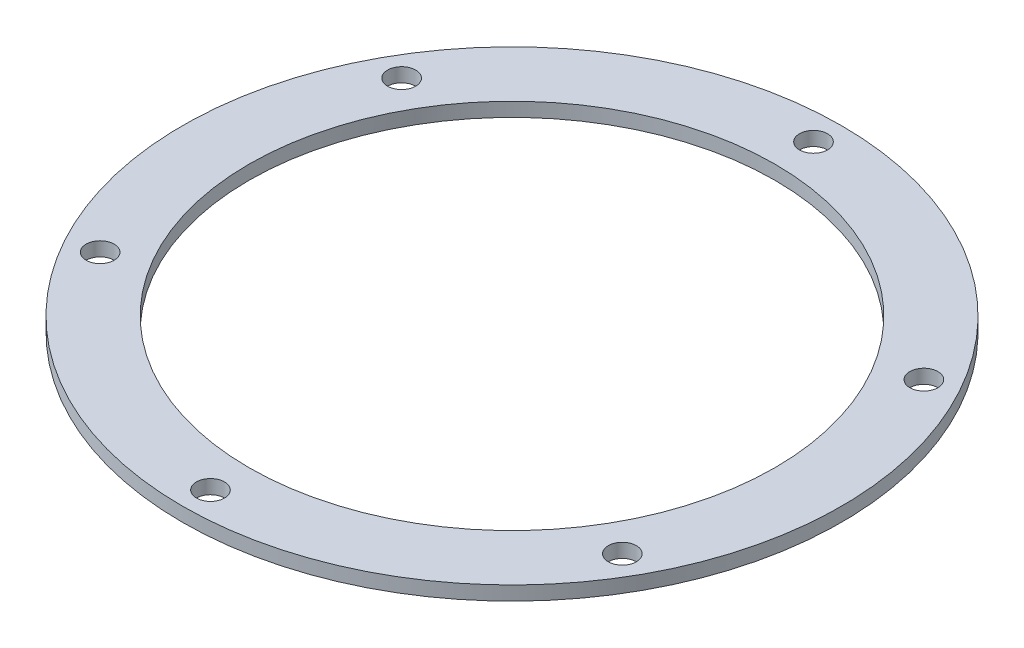
SolidWorks part; units mm, degrees
material "PLA"
ref_plane "Front Plane" through (0, 0, 0) normal (0, 0, 1) x (1, 0, 0)
ref_plane "Top Plane" through (0, 0, 0) normal (0, 1, 0) x (1, 0, 0)
ref_plane "Right Plane" through (0, 0, 0) normal (1, 0, 0) x (0, 0, -1)
sketch "Sketch1" plane through (0, 0, 0) normal (0, 1, 0) x (1, 0, 0)
  circle A0 centre (0, 0) radius 47
  circle A1 centre (0, 0) radius 37.5
  circle A2 centre (0, 0) radius 43 construction
  circle A3 centre (0, 43) radius 2
  circle A4 centre (37.2391, 21.5) radius 2
  circle A5 centre (37.2391, -21.5) radius 2
  circle A6 centre (0, -43) radius 2
  circle A7 centre (-37.2391, -21.5) radius 2
  circle A8 centre (-37.2391, 21.5) radius 2
  point P19 (0, 0)
  dimension "D1" = 94
  dimension "D2" = 75
  dimension "D3" = 86
  dimension "D4" = 4
  dimension "D5" = 6
extrude "Boss-Extrude1" add sketch "Sketch1" along normal blind 2
equation "\"Np_b\" = 48"
equation "\"Np_s\" = 28"
equation "\"Nr_b\" = 152"
equation "\"Nr_s\" = 132"
equation "\"Ns\" = 56"
equation "\"Motor_case_ID\" = 96.8"
equation "\"Motor_case_OD_base_to_chamfer\" = 5"
equation "\"Motor_case_OD_max\" = 111.3"
equation "\"Motor_case_thickness\" = 2.5"
equation "\"air_flow_hole_offset\" = 3"
equation "\"standard_bearing_insertion_chamfer\" = 0.5"
equation "\"alpha_p_b\" = 0.8539582918412414"
equation "\"alpha_p_s\" = 0.8539582918412485"
equation "\"alpha_r_b\" = 0.8539582918412236"
equation "\"alpha_r_s\" = 0.8539582918412449"
equation "\"alpha_s\" = 0.8539582918412485"
equation "\"base_plate_thickness\" = 4"
equation "\"bearing_ID\" = 60"
equation "\"bearing_OD\" = 78"
equation "\"bearing_height\" = 10"
equation "\"bearing mount thickness\" = 8"
equation "\"bearing_retainer_thickness\" = 2"
equation "\"beta_p_b\" = 2.042083416317517"
equation "\"beta_p_s\" = 4.720654844888932"
equation "\"beta_r_b\" = 2.8921271099982366"
equation "\"beta_r_s\" = 3.071552947318853"
equation "\"beta_s\" = 1.5063691306032174"
equation "\"carrier_PCD\" = 52.0"
equation "\"carrier_bearing_step_width\" = 1.5"
equation "\"carrier_small_ring_inner_bearing_ID\" = 20"
equation "\"carrier_small_ring_inner_bearing_OD\" = 32"
equation "\"carrier_small_ring_inner_bearing_flap\" = 2"
equation "\"carrier_small_ring_inner_bearing_height\" = 7"
equation "\"carrier_thickness\" = 4"
equation "\"carrier_trapezoidal_support_hole_PCD_offset_bearing_ID\" = 4"
equation "\"carrier_trapezoidal_support_hole_dia\" = 3"
equation "\"carrier_trapezoidal_support_hole_socket_head_dia\" = 5.5"
equation "\"carrier_trapezoidal_support_hole_wrench_size\" = 5.5"
equation "\"carrier_trapezoidal_support_sun_offset\" = 5"
equation "\"case_dist\" = 6.5"
equation "\"case_mounting_PCD\" = 103.8"
equation "\"case_mounting_bolt_depth\" = 4.5"
equation "\"case_mounting_hole_allen_socket_dia\" = 5.5"
equation "\"case_mounting_hole_dia\" = 3"
equation "\"case_mounting_hole_shift\" = 1.0"
equation "\"case_mounting_nut_clearance\" = 2"
equation "\"case_mounting_nut_thickness\" = 2.4"
equation "\"case_mounting_surface_height\" = 4"
equation "\"case_mounting_wrench_size\" = 5.5"
equation "\"central_hole_offset_from_motor_mount_PCD\" = 5"
equation "\"clearance_case_mount_holes_shell_thickness\" = 1"
equation "\"clearance_motor_and_case\" = 5"
equation "\"clearance_planet\" = 1.5"
equation "\"clearance_sun_coupler_sec_carrier\" = 1.5"
equation "\"clr_tip_root\" = 0.125"
equation "\"clr_tip_root_s\" = 0.125"
equation "\"db_p_b\" = 22.552622898861802"
equation "\"db_p_s\" = 13.155696691002717"
equation "\"db_r_b\" = 71.41663917972905"
equation "\"db_r_s\" = 62.01971297186996"
equation "\"db_s\" = 26.311393382005434"
equation "\"dp_p_b\" = 24.0"
equation "\"dp_p_s\" = 14.0"
equation "\"dp_r_b\" = 76.0"
equation "\"dp_r_s\" = 66.0"
equation "\"dp_s\" = 28.0"
equation "\"driver_lower_holes_dist_from_center\" = 13"
equation "\"driver_mount_height\" = 6"
equation "\"driver_mount_holes_dia\" = 3"
equation "\"driver_mount_inserts_OD\" = 4.8"
equation "\"driver_mount_thickness\" = 1.5"
equation "\"driver_side_holes_dist_from_center\" = 22.5"
equation "\"driver_upper_holes_dist_from_center\" = 29"
equation "\"fw_p_b\" = 9.918018611286483"
equation "\"fw_p_s\" = 15.90536252346366"
equation "\"fw_r_b\" = 9.918018611286483"
equation "\"fw_r_s\" = 14.40536252346366"
equation "\"fw_s_calc\" = 2.7970255760332914"
equation "\"fw_s_used\" = 33.32338113475014"
equation "\"gear_casing_big_ring_to_bearing_dist\" = 24.90536252346366"
equation "\"gear_casing_thickness\" = 4"
equation "\"h_a\" = 0.5"
equation "\"h_b\" = 0.625"
equation "\"h_f\" = 0.625"
equation "\"module\" = 0.5"
equation "\"motor_OD\" = 86.8"
equation "\"motor_case_OD_base\" = 101.8"
equation "\"motor_height\" = 26.5"
equation "\"motor_mount_hole_PCD\" = 32"
equation "\"motor_mount_hole_dia\" = 4"
equation "\"motor_mount_hole_num\" = 4"
equation "\"motor_output_hole_CSK_OD\" = 8"
equation "\"motor_output_hole_CSK_head_height\" = 2.0"
equation "\"motor_output_hole_PCD\" = 23"
equation "\"motor_output_hole_dia\" = 4"
equation "\"motor_output_hole_num\" = 4"
equation "\"num_planet\" = 4"
equation "\"output_mounting_PCD\" = 86"
equation "\"output_mounting_hole_dia\" = 4"
equation "\"output_mounting_nut_depth\" = 3"
equation "\"output_mounting_nut_thickness\" = 3.2"
equation "\"output_mounting_nut_wrench_size\" = 7"
equation "\"pattern_bulge_dia\" = 3"
equation "\"pattern_depth\" = 2"
equation "\"pattern_num_bulge\" = 18"
equation "\"pattern_offset_from_motor_case_OD_base\" = 3"
equation "\"planet_bearing_OD\" = 12"
equation "\"planet_bearing_width\" = 3.5"
equation "\"planet_bore\" = 10"
equation "\"planet_pin_bolt_dia\" = 5"
equation "\"planet_pin_bolt_wrench_size\" = 8"
equation "\"planet_pin_socket_head_dia\" = 8.5"
equation "\"planet_shaft_dia\" = 8"
equation "\"planet_shaft_step_offset\" = 1"
equation "\"pressure_angle\" = 20.0"
equation "\"pressure angle\" = 20.0"
equation "\"ring_OD_b\" = 86.0"
equation "\"ring_radial_thickness\" = 5"
equation "\"ring_to_chamfer_clearance\" = 1.5"
equation "\"sec_carrier_thickness\" = 5"
equation "\"small_ring_case_thickness\" = 4"
equation "\"small_ring_output_wall_thickness\" = 5"
equation "\"small_ring_output_wall_to_bearing_shaft_attachement_hole_CSK_OD\" = 8"
equation "\"small_ring_output_wall_to_bearing_shaft_attachement_hole_CSK_head_height\" = 2.0"
equation "\"small_ring_output_wall_to_bearing_shaft_attachement_hole_depth\" = 6.5"
equation "\"small_ring_output_wall_to_bearing_shaft_attachement_hole_dia\" = 4"
equation "\"small_ring_output_wall_to_bearing_shaft_attachement_hole_num\" = 3"
equation "\"small_ring_output_wall_to_bearing_shaft_attachement_hole_pcd\" = 12"
equation "\"small_ring_output_wall_to_bearing_shaft_attachement_nut_thickness\" = 3.2"
equation "\"small_ring_output_wall_to_bearing_shaft_attachement_nut_wrench\" = 7"
equation "\"standard_clearance_1_5mm\" = 1.5"
equation "\"standard_fillet_1_5mm\" = 1.5"
equation "\"sun_central_bolt_dia\" = 5"
equation "\"sun_central_bolt_socket_head_dia\" = 8.5"
equation "\"sun_coupler_hub_thickness\" = 4"
equation "\"sun_hub_dia\" = 30.0"
equation "\"sun_shaft_bearing_ID\" = 8"
equation "\"sun_shaft_bearing_OD\" = 16"
equation "\"sun_shaft_bearing_width\" = 5"
equation "\"wire_slot_dist_from_center\" = 38"
equation "\"wire_slot_length\" = 10"
equation "\"wire_slot_radius\" = 2.5"
equation "\"tight_clearance_3DP\" = 0.4"
equation "\"loose_clearance_3DP\" = 0.8"
equation "\"D1@Sketch1\"= \"bearing_OD\" + \"bearing mount thickness\" * 2"
equation "\"D2@Sketch1\"=\"bearing_OD\" -  \"standard_clearance_1_5mm\"*2"
equation "\"D3@Sketch1\"= \"output_mounting_PCD\""
equation "\"D4@Sketch1\"= \"output_mounting_hole_dia\""
equation "\"D1@Boss-Extrude1\"= \"bearing_retainer_thickness\""
